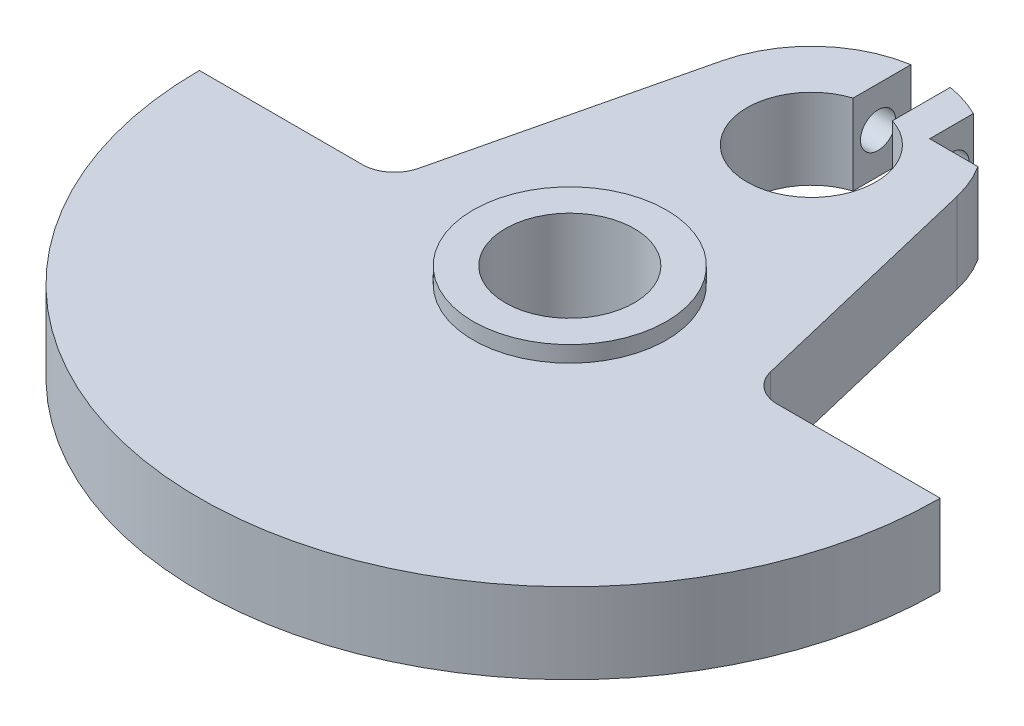
SolidWorks part; units mm, degrees
ref_plane "Front Plane" through (0, 0, 0) normal (0, 0, 1) x (1, 0, 0)
ref_plane "Top Plane" through (0, 0, 0) normal (0, 1, 0) x (1, 0, 0)
ref_plane "Right Plane" through (0, 0, 0) normal (1, 0, 0) x (0, 0, -1)
sketch "Sketch1" plane through (0, 0, 0) normal (0, 1, 0) x (1, 0, 0)
  line L0 (-23, 0) -> (-12.878, 0)
  line L1 (0, -23) -> (0, 23) construction
  line L2 (23, 0) -> (12.878, 0)
  line L3 (-10.9329, 1.5347) -> (-7.2942, 16.745)
  line L4 (10.9329, 1.5347) -> (7.2942, 16.745)
  arc A0 (-23, 0) -> (23, 0) centre (0, 0) ccw
  arc A1 (7.2942, 16.745) -> (-7.2942, 16.745) centre (0, 15) ccw
  arc A2 (12.878, 0) -> (10.9329, 1.5347) centre (12.878, 2) cw
  arc A3 (-12.878, 0) -> (-10.9329, 1.5347) centre (-12.878, 2) ccw
  point P8 (0, 0)
  point P14 (11.3, 0)
  point P17 (-11.3, 0)
  dimension "D1" = 46
  dimension "D3" = 15
  dimension "D5" = 2
  dimension "D2" = 11.7
  dimension "D4" = 15
extrude "Boss-Extrude1" add sketch "Sketch1" along normal blind 5
sketch "Sketch2" plane through (0, 5, 0) normal (0, 1, 0) x (1, 0, 0)
  circle A0 centre (0, 0) radius 6
  dimension "D1" = 12
extrude "Boss-Extrude2" add sketch "Sketch2" along normal blind 1
sketch "Sketch3" plane through (0, 6, 0) normal (0, 1, 0) x (1, 0, 0)
  circle A0 centre (0, 0) radius 4
  dimension "D1" = 8
extrude "Cut-Extrude1" cut sketch "Sketch3" against normal through all
sketch "Sketch4" plane through (0, 5, 0) normal (0, 1, 0) x (1, 0, 0)
  line L0 (0, 0) -> (0, 22.5) construction
  line L1 (-1.2207, 18.8092) -> (-1.2207, 22.4)
  line L2 (1.2207, 18.8092) -> (1.2207, 22.4)
  line L6 (-12.878, 0) -> (-23, 0) construction
  arc A0 (-1.2207, 18.8092) -> (1.2207, 18.8092) centre (0, 15) ccw
  arc A1 (7.2942, 16.745) -> (-7.2942, 16.745) centre (0, 15) ccw construction
  arc A2 (-1.2207, 22.4) -> (1.2207, 22.4) centre (0, 15) cw
  dimension "D2" = 8
  dimension "D1" = 15
  dimension "D3" = 22.4
extrude "Cut-Extrude2" cut sketch "Sketch4" against normal blind 10
sketch "Sketch5" plane through (0, 5, 0) normal (0, 1, 0) x (1, 0, 0)
  line L0 (3.3443, 19) -> (6.3443, 19)
  line L1 (3.3443, 19) -> (3.3443, 21.7131)
  arc A3 (7.2942, 16.745) -> (1.2207, 22.4) centre (0, 15) ccw construction
  arc A4 (6.3443, 19) -> (3.3443, 21.7131) centre (0, 15) ccw
  point P10 (6.3443, 18.6821)
  point P12 (3.083, 21.7131)
  dimension "D1" = 3
extrude "Cut-Extrude3" cut sketch "Sketch5" against normal blind 10
sketch "Sketch7" plane through (0, 0, 0) normal (1, 0, 0) x (0, 0, -1)
  line L0 (21.7131, 5) -> (19, 5) construction
  line L2 (21.7131, 0) -> (21.7131, 5) construction
  circle A0 centre (20.3581, 2.5) radius 1.0922
  dimension "D2" = 1.355
  dimension "D3" = 2.1844
  dimension "D1" = 2.5
extrude "Cut-Extrude4" cut sketch "Sketch7" against normal through all both and the other way through all
